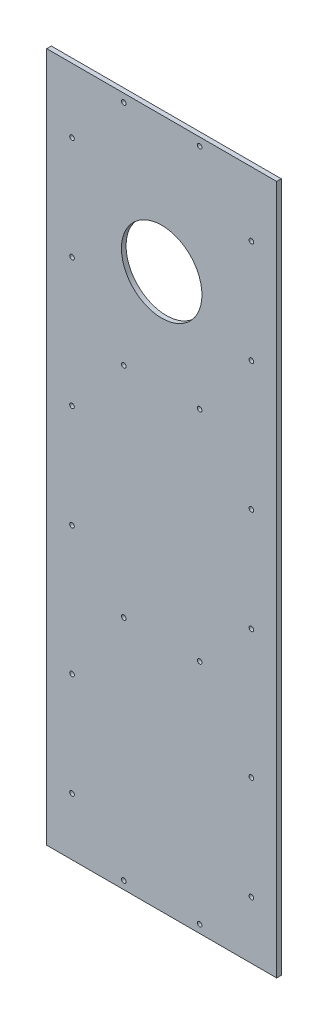
SolidWorks part; units mm, degrees
material "Alumina"
ref_plane "Front Plane" through (0, 0, 0) normal (0, 0, 1) x (1, 0, 0)
ref_plane "Top Plane" through (0, 0, 0) normal (0, 1, 0) x (1, 0, 0)
ref_plane "Right Plane" through (0, 0, 0) normal (1, 0, 0) x (0, 0, -1)
sketch "Sketch1" plane through (0, 0, 0) normal (0, 0, 1) x (1, 0, 0)
  line L1 (50, -150) -> (-50, -150)
  line L2 (50, -150) -> (50, 150)
  line L3 (50, 150) -> (-50, 150)
  line L4 (-50, -150) -> (-50, 150)
  line L5 (50, -150) -> (-50, 150) construction
  line L6 (50, 150) -> (-50, -150) construction
  point P0 (0, 0)
  dimension "D1" = 100
  dimension "D2" = 300
extrude "Boss-Extrude1" add sketch "Sketch1" along normal blind 2
sketch "Sketch2" plane through (0, 0, 2) normal (0, 0, 1) x (1, 0, 0)
  line L0 (-50, 150) -> (-50, -150) construction
  line L1 (50, 150) -> (-50, 150) construction
  line L2 (-50, -150) -> (50, -150) construction
  line L4 (0, -1.1) -> (0, 1.1) construction
  line L5 (-39, 122) -> (-39, 21) construction
  circle A0 centre (-39, 122) radius 1
  circle A1 centre (-39, 77) radius 1
  circle A2 centre (39, 122) radius 1
  circle A3 centre (39, 77) radius 1
  circle A4 centre (-39, 21) radius 1
  circle A5 centre (-39, -24) radius 1
  circle A6 centre (39, 21) radius 1
  circle A7 centre (39, -24) radius 1
  circle A8 centre (-39, -80) radius 1
  circle A9 centre (-39, -125) radius 1
  circle A10 centre (39, -80) radius 1
  circle A11 centre (39, -125) radius 1
  circle A13 centre (16.5, -146.5) radius 1
  circle A14 centre (-16.5, -146.5) radius 1
  circle A15 centre (-16.5, 146.5) radius 1
  circle A16 centre (16.5, 146.5) radius 1
  dimension "D1" = 2
  dimension "D3" = 28
  dimension "D4" = 2
  dimension "D6" = 11
  dimension "D10" = 2
  dimension "D11" = 33
  dimension "D13" = 3.5
  dimension "D14" = 78
  dimension "D15" = 11
  dimension "D5" = 3.5
  dimension "D2" = 11
  dimension "D9" = 25
  dimension "D17" = 101
  dimension "D7" = 2
  dimension "D8" = 3
  dimension "D12" = 2
extrude "Cut-Extrude1" cut sketch "Sketch2" against normal blind 10
sketch "Sketch3" plane through (0, 0, 0) normal (0, 0, -1) x (-1, 0, 0)
  line L0 (-50, 150) -> (50, 150) construction
  line L1 (-50, -150) -> (-50, 150) construction
  circle A0 centre (0, 91) radius 17.5
  dimension "D2" = 35
  dimension "D3" = 50
  dimension "D1" = 59
extrude "Cut-Extrude2" cut sketch "Sketch3" against normal blind 10
sketch "Sketch5" plane through (0, 0, 2) normal (0, 0, 1) x (1, 0, 0)
  line L0 (-16.5, 47.5) -> (-16.5, -47.5) construction
  line L1 (-16.5, -47.5) -> (16.5, -47.5) construction
  line L2 (16.5, -47.5) -> (16.5, 47.5) construction
  line L3 (16.5, 47.5) -> (-16.5, 47.5) construction
  line L4 (-16.5, 146.5) -> (-16.5, 47.5) construction
  line L5 (16.5, 146.5) -> (16.5, 47.5) construction
  circle A6 centre (-16.5, 47.5) radius 1
  circle A7 centre (16.5, 47.5) radius 1
  circle A8 centre (-16.5, -47.5) radius 1
  circle A9 centre (16.5, -47.5) radius 1
  circle A10 centre (-16.5, 146.5) radius 1 construction
  circle A11 centre (16.5, 146.5) radius 1 construction
  dimension "D1" = 99
  dimension "D3" = 2
  dimension "D4" = 2
  dimension "D5" = 2
  dimension "D6" = 2
  dimension "D2" = 95
extrude "Cut-Extrude3" cut sketch "Sketch5" against normal blind 10
